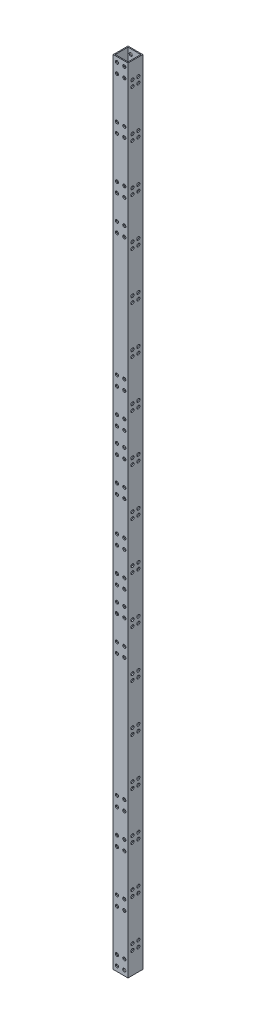
SolidWorks part; units mm, degrees
ref_plane "前视基准面" through (0, 0, 0) normal (0, 0, 1) x (1, 0, 0)
ref_plane "上视基准面" through (0, 0, 0) normal (0, 1, 0) x (1, 0, 0)
ref_plane "右视基准面" through (0, 0, 0) normal (1, 0, 0) x (0, 0, -1)
other "Configuration Table"
sketch "草图1" plane through (0, 0, 0) normal (0, 1, 0) x (1, 0, 0)
  line L1 (6.5, -6.5) -> (-6.5, -6.5)
  line L2 (6.5, -6.5) -> (6.5, 6.5)
  line L3 (6.5, 6.5) -> (-6.5, 6.5)
  line L4 (-6.5, -6.5) -> (-6.5, 6.5)
  line L5 (6.5, -6.5) -> (-6.5, 6.5) construction
  line L6 (6.5, 6.5) -> (-6.5, -6.5) construction
  line L7 (7.5, -7.5) -> (-7.5, -7.5)
  line L8 (7.5, -7.5) -> (7.5, 7.5)
  line L9 (7.5, 7.5) -> (-7.5, 7.5)
  line L10 (-7.5, -7.5) -> (-7.5, 7.5)
  line L11 (7.5, -7.5) -> (-7.5, 7.5) construction
  line L12 (7.5, 7.5) -> (-7.5, -7.5) construction
  point P0 (0, 0)
  point P6 (0, 0)
  dimension "D1" = 15
  dimension "D2" = 13
extrude "凸台-拉伸1" add sketch "草图1" along normal blind 805
sketch "草图2" plane through (0, 0, 7.5) normal (0, 0, 1) x (1, 0, 0)
  line L0 (0, 804.3358) -> (0, 762.8538) construction
  line L1 (-7.5, 742.5) -> (7.5, 742.5) construction
  line L2 (-7.5, 805) -> (-7.5, 0) construction
  line L3 (7.5, 805) -> (7.5, 0) construction
  line L4 (-7.5, 805) -> (7.5, 805) construction
  line L5 (-7.5, 402.5) -> (7.5, 402.5) construction
  line L6 (-7.5, 62.5) -> (7.5, 62.5) construction
  line L7 (-7.5, 672.5) -> (7.5, 672.5) construction
  line L8 (-7.5, 690) -> (7.5, 690) construction
  line L9 (-7.5, 655) -> (7.5, 655) construction
  line L10 (-7.5, 150) -> (7.5, 150) construction
  line L11 (-7.5, 115) -> (7.5, 115) construction
  line L12 (-7.5, 132.5) -> (7.5, 132.5) construction
  line L13 (-7.5, 795) -> (7.5, 795) construction
  line L14 (-7.5, 10) -> (7.5, 10) construction
  line L15 (7.5, 302.5) -> (-7.5, 302.5) construction
  line L16 (-7.5, 0) -> (7.5, 0) construction
  line L17 (-7.5, 285) -> (7.5, 285) construction
  line L18 (-7.5, 320) -> (7.5, 320) construction
  line L19 (-7.5, 485) -> (7.5, 485) construction
  line L20 (-7.5, 520) -> (7.5, 520) construction
  line L21 (7.5, 502.5) -> (-7.5, 502.5) construction
  line L22 (-7.5, 442.3) -> (7.5, 442.3) construction
  line L23 (7.5, 459.8) -> (-7.5, 459.8) construction
  line L24 (7.5, 424.8) -> (-7.5, 424.8) construction
  line L25 (7.5, 380.2) -> (-7.5, 380.2) construction
  line L26 (7.5, 345.2) -> (-7.5, 345.2) construction
  line L27 (-7.5, 362.7) -> (7.5, 362.7) construction
  circle A0 centre (-3.75, 747.5) radius 1.6
  circle A1 centre (3.75, 747.5) radius 1.6
  circle A2 centre (-3.75, 737.5) radius 1.6
  circle A3 centre (3.75, 737.5) radius 1.6
  circle A4 centre (3.75, 67.5) radius 1.6
  circle A5 centre (-3.75, 67.5) radius 1.6
  circle A6 centre (3.75, 57.5) radius 1.6
  circle A7 centre (-3.75, 57.5) radius 1.6
  circle A8 centre (-3.75, 695) radius 1.6
  circle A9 centre (3.75, 695) radius 1.6
  circle A10 centre (3.75, 685) radius 1.6
  circle A11 centre (-3.75, 685) radius 1.6
  circle A12 centre (-3.75, 660) radius 1.6
  circle A13 centre (3.75, 660) radius 1.6
  circle A14 centre (3.75, 650) radius 1.6
  circle A15 centre (-3.75, 650) radius 1.6
  circle A16 centre (-3.75, 155) radius 1.6
  circle A17 centre (3.75, 155) radius 1.6
  circle A18 centre (3.75, 145) radius 1.6
  circle A19 centre (-3.75, 145) radius 1.6
  circle A20 centre (-3.75, 120) radius 1.6
  circle A21 centre (3.75, 120) radius 1.6
  circle A22 centre (3.75, 110) radius 1.6
  circle A23 centre (-3.75, 110) radius 1.6
  circle A24 centre (-3.75, 800) radius 1.6
  circle A25 centre (3.75, 800) radius 1.6
  circle A26 centre (3.75, 790) radius 1.6
  circle A27 centre (-3.75, 790) radius 1.6
  circle A28 centre (-3.75, 15) radius 1.6
  circle A29 centre (3.75, 15) radius 1.6
  circle A30 centre (3.75, 5) radius 1.6
  circle A31 centre (-3.75, 5) radius 1.6
  circle A32 centre (-3.75, 290) radius 1.6
  circle A33 centre (3.75, 290) radius 1.6
  circle A34 centre (3.75, 280) radius 1.6
  circle A35 centre (-3.75, 280) radius 1.6
  circle A36 centre (-3.75, 325) radius 1.6
  circle A37 centre (3.75, 325) radius 1.6
  circle A38 centre (3.75, 315) radius 1.6
  circle A39 centre (-3.75, 315) radius 1.6
  circle A40 centre (-3.75, 490) radius 1.6
  circle A41 centre (3.75, 490) radius 1.6
  circle A42 centre (3.75, 480) radius 1.6
  circle A43 centre (-3.75, 480) radius 1.6
  circle A44 centre (-3.75, 525) radius 1.6
  circle A45 centre (3.75, 525) radius 1.6
  circle A46 centre (3.75, 515) radius 1.6
  circle A47 centre (-3.75, 515) radius 1.6
  circle A48 centre (-3.75, 464.8) radius 1.6
  circle A49 centre (3.75, 464.8) radius 1.6
  circle A50 centre (3.75, 454.8) radius 1.6
  circle A51 centre (-3.75, 454.8) radius 1.6
  circle A52 centre (-3.75, 429.8) radius 1.6
  circle A53 centre (3.75, 429.8) radius 1.6
  circle A54 centre (3.75, 419.8) radius 1.6
  circle A55 centre (-3.75, 419.8) radius 1.6
  circle A56 centre (-3.75, 385.2) radius 1.6
  circle A57 centre (3.75, 385.2) radius 1.6
  circle A58 centre (3.75, 375.2) radius 1.6
  circle A59 centre (-3.75, 375.2) radius 1.6
  circle A60 centre (-3.75, 350.2) radius 1.6
  circle A61 centre (3.75, 350.2) radius 1.6
  circle A62 centre (3.75, 340.2) radius 1.6
  circle A63 centre (-3.75, 340.2) radius 1.6
  dimension "D2" = 3.2
  dimension "D5" = 132.5
  dimension "D8" = 3.75
  dimension "D7" = 3.2
  dimension "D11" = 3.2
  dimension "D15" = 3.2
  dimension "D21" = 3.2
  dimension "D1" = 62.5
  dimension "D3" = 7.5
  dimension "D4" = 10
  dimension "D6" = 17.5
  dimension "D9" = 5
  dimension "D10" = 10
  dimension "D12" = 3.75
  dimension "D13" = 5
  dimension "D14" = 302.5
  dimension "D16" = 3.75
  dimension "D17" = 17.5
  dimension "D18" = 5
  dimension "D19" = 362.7
  dimension "D20" = 17.5
  dimension "D22" = 3.75
  dimension "D23" = 5
extrude "切除-拉伸1" cut sketch "草图2" against normal up to surface (15 mm away) up to face at (0, 402.5, -7.5)
sketch "草图3" plane through (-7.5, 0, 0) normal (-1, 0, 0) x (0, 0, 1)
  line L0 (0, 809.7886) -> (0, 782.9032) construction
  line L1 (-7.5, 785) -> (7.5, 785) construction
  line L2 (-7.5, 805) -> (-7.5, 0) construction
  line L3 (7.5, 805) -> (7.5, 0) construction
  line L4 (-7.5, 805) -> (7.5, 805) construction
  circle A0 centre (-3, 788) radius 1.6
  circle A1 centre (3, 788) radius 1.6
  circle A2 centre (-3, 782) radius 1.6
  circle A3 centre (3, 782) radius 1.6
  circle A4 centre (-3, 740.5) radius 1.6
  circle A5 centre (-3, 734.5) radius 1.6
  circle A6 centre (3, 734.5) radius 1.6
  circle A7 centre (3, 740.5) radius 1.6
  circle A8 centre (-3, 693) radius 1.6
  circle A9 centre (-3, 687) radius 1.6
  circle A10 centre (3, 687) radius 1.6
  circle A11 centre (3, 693) radius 1.6
  circle A12 centre (-3, 645.5) radius 1.6
  circle A13 centre (-3, 639.5) radius 1.6
  circle A14 centre (3, 639.5) radius 1.6
  circle A15 centre (3, 645.5) radius 1.6
  circle A16 centre (-3, 598) radius 1.6
  circle A17 centre (-3, 592) radius 1.6
  circle A18 centre (3, 592) radius 1.6
  circle A19 centre (3, 598) radius 1.6
  circle A20 centre (-3, 550.5) radius 1.6
  circle A21 centre (-3, 544.5) radius 1.6
  circle A22 centre (3, 544.5) radius 1.6
  circle A23 centre (3, 550.5) radius 1.6
  circle A24 centre (-3, 503) radius 1.6
  circle A25 centre (-3, 497) radius 1.6
  circle A26 centre (3, 497) radius 1.6
  circle A27 centre (3, 503) radius 1.6
  circle A28 centre (-3, 455.5) radius 1.6
  circle A29 centre (-3, 449.5) radius 1.6
  circle A30 centre (3, 449.5) radius 1.6
  circle A31 centre (3, 455.5) radius 1.6
  circle A32 centre (-3, 408) radius 1.6
  circle A33 centre (-3, 402) radius 1.6
  circle A34 centre (3, 402) radius 1.6
  circle A35 centre (3, 408) radius 1.6
  circle A36 centre (-3, 360.5) radius 1.6
  circle A37 centre (-3, 354.5) radius 1.6
  circle A38 centre (3, 354.5) radius 1.6
  circle A39 centre (3, 360.5) radius 1.6
  circle A40 centre (-3, 313) radius 1.6
  circle A41 centre (-3, 307) radius 1.6
  circle A42 centre (3, 307) radius 1.6
  circle A43 centre (3, 313) radius 1.6
  circle A44 centre (-3, 265.5) radius 1.6
  circle A45 centre (-3, 259.5) radius 1.6
  circle A46 centre (3, 259.5) radius 1.6
  circle A47 centre (3, 265.5) radius 1.6
  circle A48 centre (-3, 218) radius 1.6
  circle A49 centre (-3, 212) radius 1.6
  circle A50 centre (3, 212) radius 1.6
  circle A51 centre (3, 218) radius 1.6
  circle A52 centre (-3, 170.5) radius 1.6
  circle A53 centre (-3, 164.5) radius 1.6
  circle A54 centre (3, 164.5) radius 1.6
  circle A55 centre (3, 170.5) radius 1.6
  circle A56 centre (-3, 123) radius 1.6
  circle A57 centre (-3, 117) radius 1.6
  circle A58 centre (3, 117) radius 1.6
  circle A59 centre (3, 123) radius 1.6
  circle A60 centre (-3, 75.5) radius 1.6
  circle A61 centre (-3, 69.5) radius 1.6
  circle A62 centre (3, 69.5) radius 1.6
  circle A63 centre (3, 75.5) radius 1.6
  circle A64 centre (-3, 28) radius 1.6
  circle A65 centre (-3, 22) radius 1.6
  circle A66 centre (3, 22) radius 1.6
  circle A67 centre (3, 28) radius 1.6
  dimension "D2" = 3.2
  dimension "D5" = 17
  dimension "D1" = 20
  dimension "D3" = 6
  dimension "D4" = 6
extrude "切除-拉伸2" cut sketch "草图3" against normal up to surface (15 mm away) up to face at (7.5, 402.5, 0)
